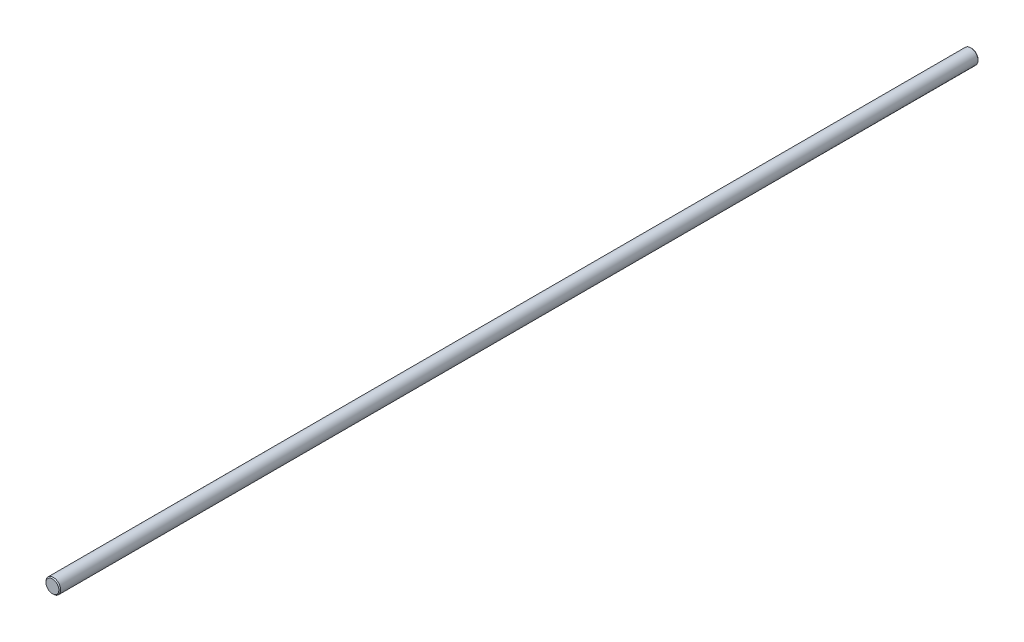
SolidWorks part; units mm, degrees
material "Plain Carbon Steel"
ref_plane "Front Plane" through (0, 0, 0) normal (0, 0, 1) x (1, 0, 0)
ref_plane "Top Plane" through (0, 0, 0) normal (0, 1, 0) x (1, 0, 0)
ref_plane "Right Plane" through (0, 0, 0) normal (1, 0, 0) x (0, 0, -1)
sketch "Sketch1" plane through (0, 0, 0) normal (0, 0, 1) x (1, 0, 0)
  circle A0 centre (0, 0) radius 4
  dimension "D1" = 8
extrude "Boss-Extrude1" add sketch "Sketch1" along normal blind 500
chamfer "Chamfer1" distance 0.5 angle 45 2 edges at (4, 0, 0) (4, 0, 500)
